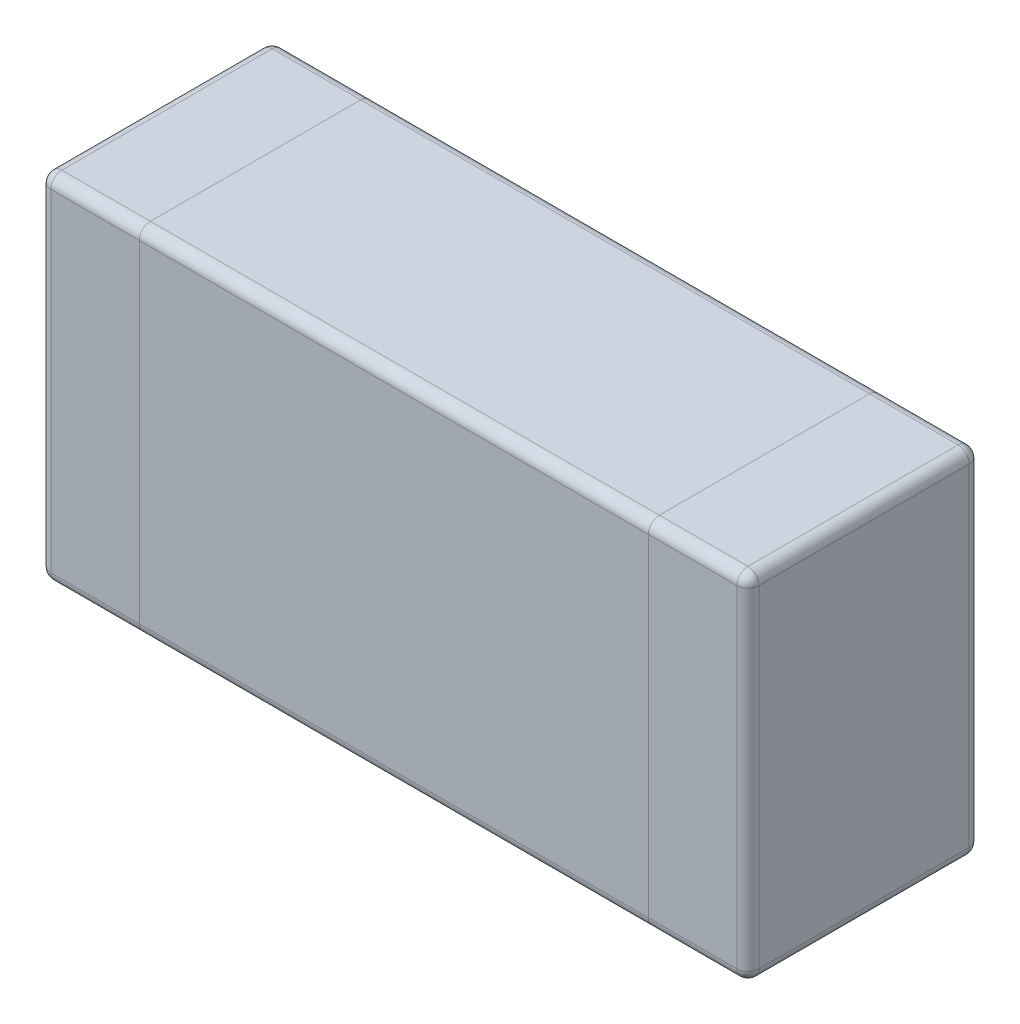
SolidWorks part; units mm, degrees
ref_plane "Front Plane" through (0, 0, 0) normal (0, 0, 1) x (1, 0, 0)
ref_plane "Top Plane" through (0, 0, 0) normal (0, 1, 0) x (1, 0, 0)
ref_plane "Right Plane" through (0, 0, 0) normal (1, 0, 0) x (0, 0, -1)
sketch "Sketch1" plane through (0, 0, 0) normal (0, 1, 0) x (1, 0, 0)
  line L1 (-1.6, -0.8) -> (1.6, -0.8)
  line L2 (-1.6, -0.8) -> (-1.6, 0.8)
  line L3 (-1.6, 0.8) -> (1.6, 0.8)
  line L4 (1.6, -0.8) -> (1.6, 0.8)
  line L5 (-1.6, -0.8) -> (1.6, 0.8) construction
  line L6 (-1.6, 0.8) -> (1.6, -0.8) construction
  point P0 (0, 0)
  dimension "D1" = 3.2
  dimension "D2" = 1.6
extrude "Extrude1" add sketch "Sketch1" along normal blind 1.05
fillet "Fillet1" radius 0.05 12 edges at (1.6, 0.525, -0.8) (-1.6, 0.525, -0.8) (-1.6, 0.525, 0.8) (1.6, 0.525, 0.8) (0, 1.05, 0.8) (-1.6, 1.05, 0) (0, 1.05, -0.8) (1.6, 1.05, 0) (0, 0, -0.8) (-1.6, 0, 0) (0, 0, 0.8) (1.6, 0, 0)
sketch "Sketch2" plane through (0, 0, 0) normal (0, 1, 0) x (1, 0, 0)
  line L0 (-1.55, 0.8) -> (1.55, 0.8) construction
  line L1 (-1.15, -0.8) -> (1.15, -0.8)
  line L2 (-1.15, -0.8) -> (-1.15, 0.8)
  line L3 (-1.15, 0.8) -> (1.15, 0.8)
  line L4 (1.15, -0.8) -> (1.15, 0.8)
  line L5 (1.55, -0.8) -> (-1.55, -0.8) construction
  line L6 (0, 0.75) -> (0, -0.6635) construction
  line L7 (1.55, 0.75) -> (-1.55, 0.75) construction
  line L9 (-1.6, -0.75) -> (-1.6, 0.75) construction
  dimension "D1" = 0.45
split line "Split Line3"
move or copy body "Körper-Verschieben/Kopieren1" bodies to move or copy 101 copy no rotation origin (0, 0, 0) rotation axis (1, 0, 0) rotation angle 90
